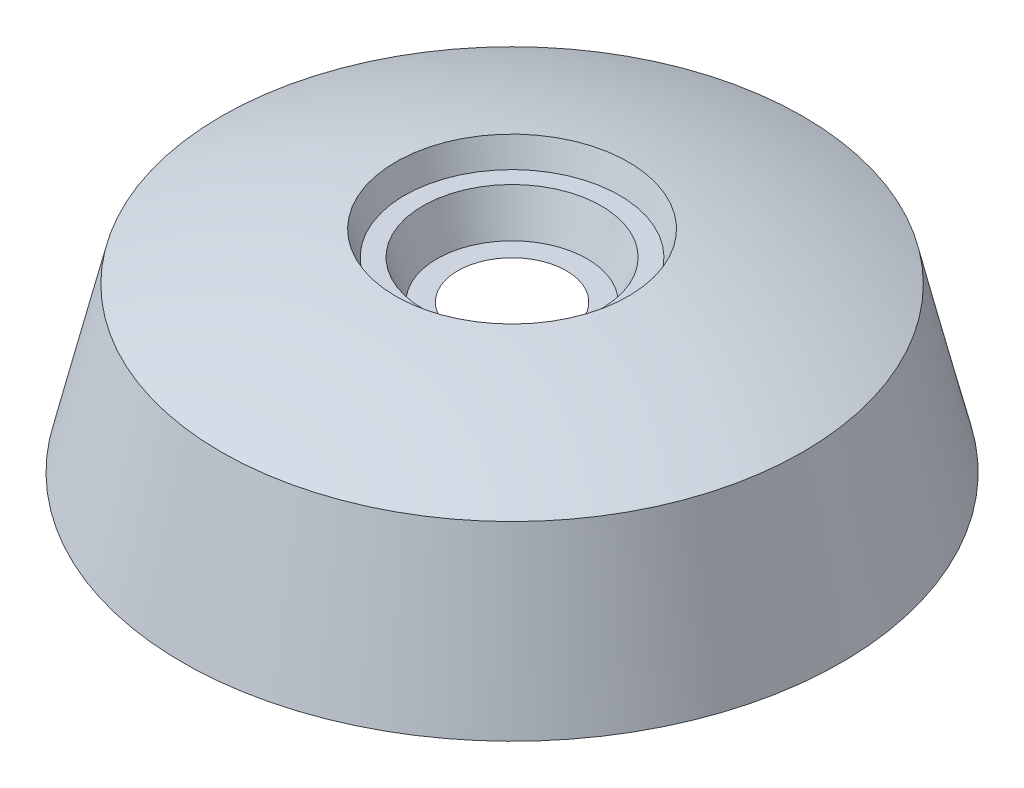
SolidWorks part; units mm, degrees
ref_plane "Front Plane" through (0, 0, 0) normal (0, 0, 1) x (1, 0, 0)
ref_plane "Top Plane" through (0, 0, 0) normal (0, 1, 0) x (1, 0, 0)
ref_plane "Right Plane" through (0, 0, 0) normal (1, 0, 0) x (0, 0, -1)
sketch "Sketch1" plane through (0, 0, 0) normal (0, 0, 1) x (1, 0, 0)
  line L0 (0, 21.4806) -> (0, -33.506) construction
  line L1 (0, 0) -> (-42.5, 0) construction
  line L2 (-7, 19) -> (-9.6801, 19)
  line L3 (-9.6801, 19) -> (-11.5, 24)
  line L4 (-11.5, 24) -> (-13.8527, 24)
  line L5 (-13.8527, 24) -> (-15, 27.1523)
  line L6 (-37.5, 21) -> (-42.5, 0)
  line L7 (-42.5, 0) -> (-7, 19)
  arc A0 (-15, 27.1523) -> (-37.5, 21) centre (-2.1804, -63.9502) ccw
  point P12 (-41.1787, 0.2042)
  dimension "D7" = 92
  dimension "D1" = 14
  dimension "D2" = 20
  dimension "D3" = 23
  dimension "D4" = 30
  dimension "D5" = 75
  dimension "D6" = 85
  dimension "D8" = 24
  dimension "D9" = 21
  dimension "D10" = 19
revolve "Revolve1" add sketch "Sketch1" angle 360 about L0
